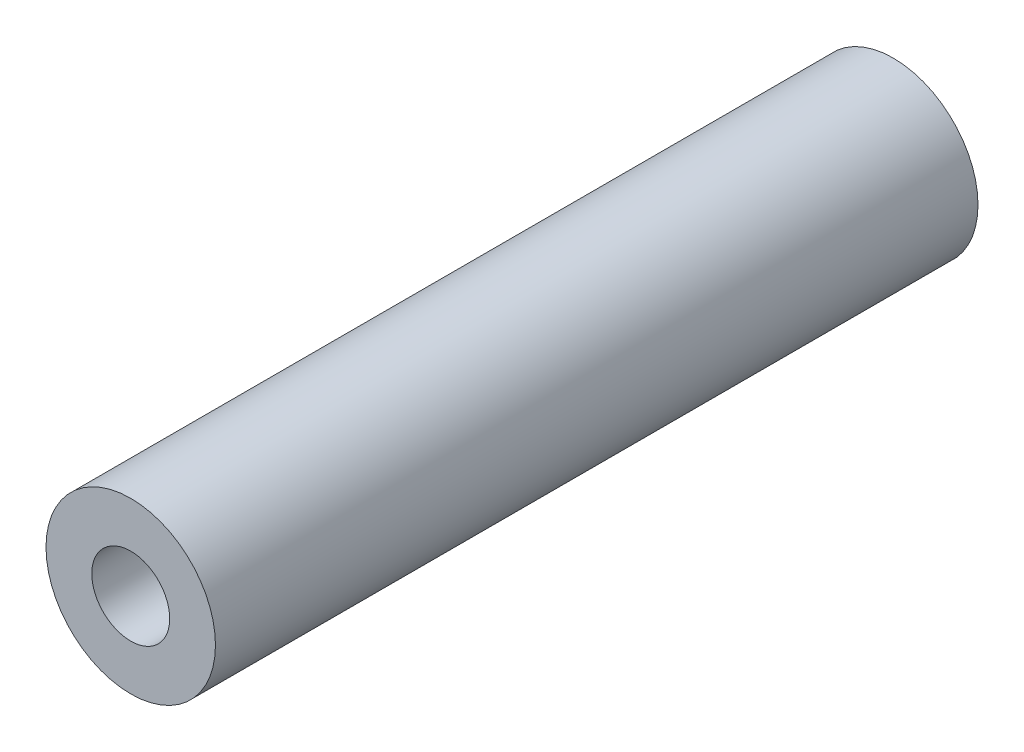
SolidWorks part; units mm, degrees
material "Alloy Steel"
ref_plane "Front Plane" through (0, 0, 0) normal (0, 0, 1) x (1, 0, 0)
ref_plane "Top Plane" through (0, 0, 0) normal (0, 1, 0) x (1, 0, 0)
ref_plane "Right Plane" through (0, 0, 0) normal (1, 0, 0) x (0, 0, -1)
sketch "Sketch1" plane through (0, 0, 0) normal (0, 0, 1) x (1, 0, 0)
  line L0 (0, 1.4605) -> (0, 3.175) construction
  line L1 (0, -1.4605) -> (0, -3.175) construction
  circle A0 centre (0, 0) radius 3.175
  circle A1 centre (0, 0) radius 1.4605
  dimension "OD" = 6.35
  dimension "ID" = 2.921
sketch "Sketch2" plane through (0, 0, 0) normal (1, 0, 0) x (0, 0, -1)
  line L0 (-14.2875, 1.4605) -> (14.2875, 1.4605) construction
  line L1 (-14.2875, -1.4605) -> (14.2875, -1.4605) construction
  line L2 (-14.2875, -3.175) -> (14.2875, -3.175) construction
  line L3 (-14.2875, 3.175) -> (14.2875, 3.175) construction
  dimension "Length" = 28.575
extrude "Extrude1" add sketch "Sketch1" along normal up to vertex (14.2875 mm away) and the other way up to vertex (14.2875 mm away) up to point (0, 1.4605, 14.2875) other way up to point (0, 1.4605, -14.2875)
sketch "Sketch3" plane through (0, 0, 14.2875) normal (0, 0, 1) x (1, 0, 0)
  circle A0 centre (0, 0) radius 1.4605 construction
  circle A3 centre (0, 0) radius 1.4605
  point P3 (-1.4605, 0)
